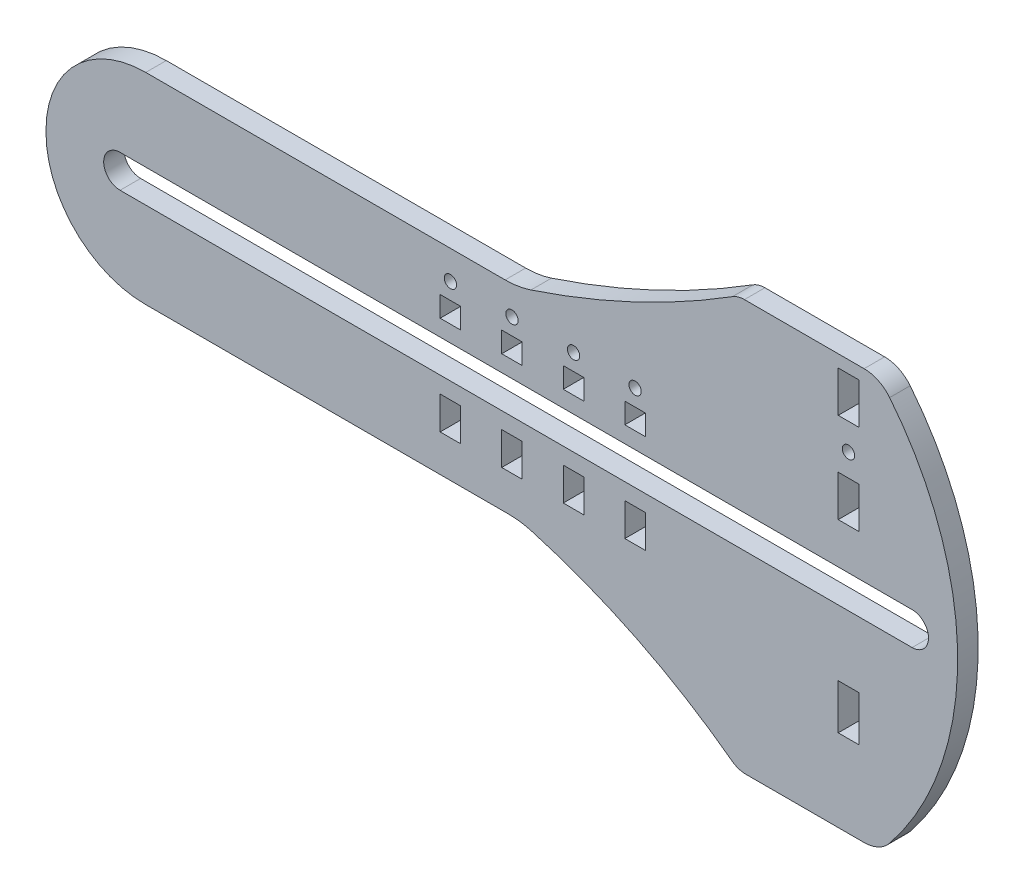
SolidWorks part; units mm, degrees
ref_plane "Plano frontal" through (0, 0, 0) normal (0, 0, 1) x (1, 0, 0)
ref_plane "Plano superior" through (0, 0, 0) normal (0, 1, 0) x (1, 0, 0)
ref_plane "Plano direito" through (0, 0, 0) normal (1, 0, 0) x (0, 0, -1)
sketch "Model" plane through (0, 0, 0) normal (0, 0, 1) x (1, 0, 0)
  line L0 (-180.6987, 44) -> (-209.5393, 44)
  line L1 (-267.2831, 70) -> (-355.9036, 70)
  line L2 (-380.0531, 94.1495) -> (-380.0531, 94.6914)
  line L3 (-355.7446, 119) -> (-268.1691, 119)
  line L4 (-209.8595, 144) -> (-180.6987, 144)
  line L5 (-279, 108) -> (-284, 108)
  line L6 (-284, 108) -> (-284, 103)
  line L7 (-284, 103) -> (-279, 103)
  line L8 (-279, 103) -> (-279, 108)
  line L9 (-279, 87) -> (-284, 87)
  line L10 (-284, 87) -> (-284, 79)
  line L11 (-284, 79) -> (-279, 79)
  line L12 (-279, 79) -> (-279, 87)
  line L13 (-239, 108) -> (-239, 103)
  line L14 (-239, 103) -> (-234, 103)
  line L15 (-234, 103) -> (-234, 108)
  line L16 (-234, 108) -> (-239, 108)
  line L17 (-239, 79) -> (-234, 79)
  line L18 (-234, 79) -> (-234, 87)
  line L19 (-234, 87) -> (-239, 87)
  line L20 (-239, 87) -> (-239, 79)
  line L21 (-254, 79) -> (-249, 79)
  line L22 (-249, 79) -> (-249, 87)
  line L23 (-249, 87) -> (-254, 87)
  line L24 (-254, 87) -> (-254, 79)
  line L25 (-254, 103) -> (-249, 103)
  line L26 (-249, 103) -> (-249, 108)
  line L27 (-249, 108) -> (-254, 108)
  line L28 (-254, 108) -> (-254, 103)
  line L29 (-187, 64) -> (-182, 64)
  line L30 (-182, 64) -> (-182, 75)
  line L31 (-182, 75) -> (-187, 75)
  line L32 (-187, 75) -> (-187, 64)
  line L33 (-187, 131) -> (-182, 131)
  line L34 (-182, 131) -> (-182, 141)
  line L35 (-182, 141) -> (-187, 141)
  line L36 (-187, 141) -> (-187, 131)
  line L37 (-187, 109) -> (-182, 109)
  line L38 (-182, 109) -> (-182, 119)
  line L39 (-182, 119) -> (-187, 119)
  line L40 (-187, 119) -> (-187, 109)
  line L41 (-264, 87) -> (-269, 87)
  line L42 (-269, 87) -> (-269, 79)
  line L43 (-269, 79) -> (-264, 79)
  line L44 (-264, 79) -> (-264, 87)
  line L45 (-264, 108) -> (-269, 108)
  line L46 (-269, 108) -> (-269, 103)
  line L47 (-269, 103) -> (-264, 103)
  line L48 (-264, 103) -> (-264, 108)
  line L49 (-362, 91) -> (-169, 91)
  line L50 (-169, 99) -> (-362, 99)
  circle A0 centre (-281.5, 112) radius 1.5
  circle A1 centre (-184.5, 124.5) radius 1.5
  circle A2 centre (-251.5, 112) radius 1.5
  circle A3 centre (-236.5, 112) radius 1.5
  circle A4 centre (-266.5, 112) radius 1.5
  arc A5 (-174.4672, 46.9832) -> (-174.4672, 141.0168) centre (-232.8684, 94) ccw
  arc A6 (-180.6987, 44) -> (-174.4672, 46.9832) centre (-180.6987, 52) ccw
  arc A7 (-212.8182, 45.0843) -> (-209.5393, 44) centre (-209.5393, 49.5) ccw
  arc A8 (-212.8182, 45.0843) -> (-261.807, 69.2357) centre (-303.4173, -76.9269) ccw
  arc A9 (-261.807, 69.2357) -> (-267.2831, 70) centre (-267.2831, 50) ccw
  arc A10 (-380.0531, 94.1495) -> (-355.9036, 70) centre (-355.9036, 94.1495) ccw
  arc A11 (-355.7446, 119) -> (-380.0531, 94.6914) centre (-355.7446, 94.6914) ccw
  arc A12 (-268.1691, 119) -> (-261.8807, 120.0143) centre (-268.1691, 139) ccw
  arc A13 (-261.8807, 120.0143) -> (-212.7864, 143.1566) centre (-332.7767, 334.06) ccw
  arc A14 (-209.8595, 144) -> (-212.7864, 143.1566) centre (-209.8595, 138.5) ccw
  arc A15 (-174.4672, 141.0168) -> (-180.6987, 144) centre (-180.6987, 136) ccw
  arc A16 (-169, 91) -> (-169, 99) centre (-169, 95) ccw
  arc A17 (-362, 99) -> (-362, 91) centre (-362, 95) ccw
extrude "Ressalto-extrusão1" add sketch "Model" along normal blind 5
